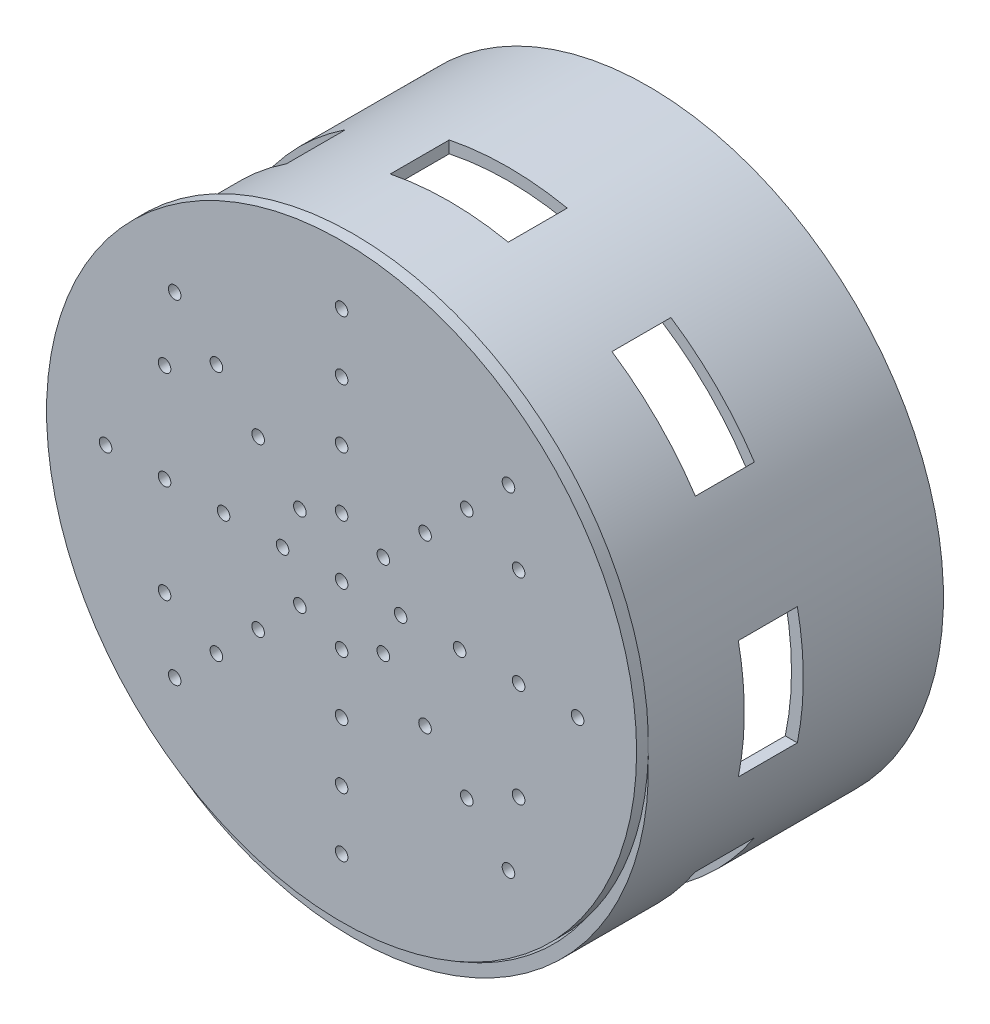
SolidWorks part; units mm, degrees
ref_plane "Front Plane" through (0, 0, 0) normal (0, 0, 1) x (1, 0, 0)
ref_plane "Top Plane" through (0, 0, 0) normal (0, 1, 0) x (1, 0, 0)
ref_plane "Right Plane" through (0, 0, 0) normal (1, 0, 0) x (0, 0, -1)
sketch "Sketch1" plane through (0, 0, 0) normal (0, 0, 1) x (1, 0, 0)
  line L0 (11.0336, -98.8354) -> (101.0336, -98.8354) construction
  line L1 (101.0336, -73.8354) -> (11.0336, -73.8354) construction
  line L2 (101.0336, -73.8354) -> (101.0336, -123.8354) construction
  line L3 (101.0336, -123.8354) -> (11.0336, -123.8354) construction
  line L4 (11.0336, -73.8354) -> (11.0336, -123.8354) construction
  circle A0 centre (56.0336, -98.8354) radius 75
  circle A1 centre (11.0336, -73.8354) radius 1.6
  circle A2 centre (101.0336, -73.8354) radius 1.6
  circle A3 centre (11.0336, -123.8354) radius 1.6
  circle A4 centre (101.0336, -123.8354) radius 1.6
extrude "Boss-Extrude1" add sketch "Sketch1" along normal blind 3
sketch "Sketch2" plane through (0, 0, 0) normal (0, 0, -1) x (-1, 0, 0)
  circle A0 centre (-56.0336, -103.8354) radius 75
  circle A1 centre (-56.0336, -103.8354) radius 72
  dimension "D1" = 3
extrude "Boss-Extrude2" add sketch "Sketch2" along normal blind 75
ref_plane "Plane1" through (0, -23.8354, 0) normal (0, 1, 0) x (1, 0, 0)
sketch "Sketch3" plane through (0, -23.8354, 0) normal (0, 1, 0) x (1, 0, 0)
  line L0 (46.2836, 31.87) -> (65.7836, 31.87) construction
  line L2 (41.0336, 24.37) -> (71.0336, 24.37)
  line L3 (41.0336, 24.37) -> (41.0336, 39.37)
  line L4 (41.0336, 39.37) -> (71.0336, 39.37)
  line L5 (71.0336, 24.37) -> (71.0336, 39.37)
  line L6 (41.0336, 24.37) -> (71.0336, 39.37) construction
  line L7 (41.0336, 39.37) -> (71.0336, 24.37) construction
  point P4 (56.0336, 31.87)
extrude "Cut-Extrude1" cut sketch "Sketch3" against normal blind 14
pattern_circular "CirPattern1" count 8 over 360 about axis through (56.0336, -103.8354, 0) along (0, 0, 1) of "Cut-Extrude1"
sketch "Sketch4" plane through (0, 0, 3) normal (0, 0, 1) x (1, 0, 0)
  line L0 (-18.9664, -98.8354) -> (131.0336, -98.8354) construction
  line L1 (56.0336, -23.8354) -> (56.0336, -173.8354) construction
  circle A0 centre (56.0336, -98.8354) radius 75 construction
  circle A1 centre (56.0336, -98.8354) radius 1.6
extrude "Cut-Extrude2" cut sketch "Sketch4" against normal blind 3
pattern_linear "LPattern2" count 5 spacing 15 along (0, 1, 0) of "Cut-Extrude2"
pattern_circular "CirPattern2" count 8 over 360 about axis through (56.0336, -98.8354, 0) along (0, 0, 1) of "LPattern2"
